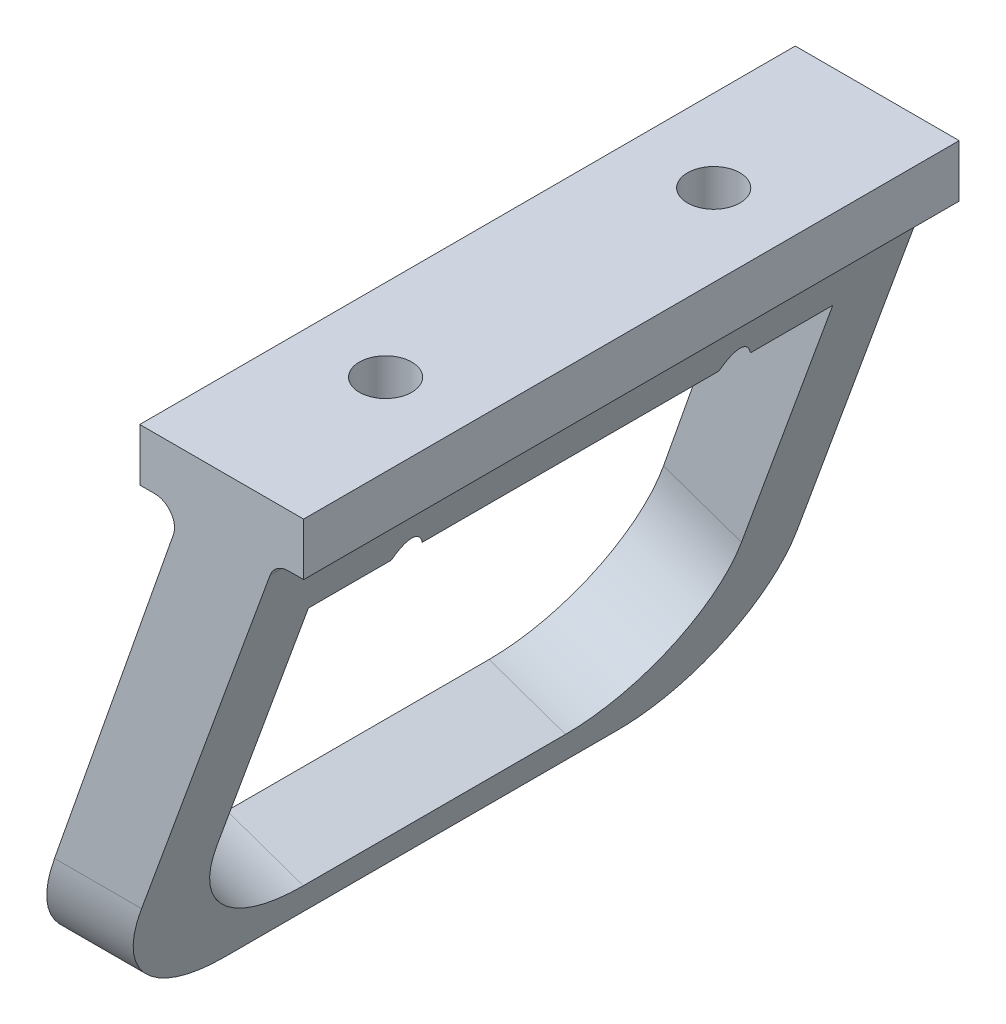
SolidWorks part; units mm, degrees
material "PETG"
ref_plane "Front Plane" through (0, 0, 0) normal (0, 0, 1) x (1, 0, 0)
ref_plane "Top Plane" through (0, 0, 0) normal (0, 1, 0) x (1, 0, 0)
ref_plane "Right Plane" through (0, 0, 0) normal (1, 0, 0) x (0, 0, -1)
sketch "Sketch1" plane through (0, 0, 0) normal (0, 0, 1) x (1, 0, 0)
  line L0 (0, 0) -> (0, 8)
  line L1 (0, 8) -> (25, 8)
  line L2 (25, 8) -> (25, 0)
  line L3 (25, 0) -> (22.7, 0)
  line L4 (19.8809, -1.9739) -> (-7, -75.8287)
  line L5 (-7, -75.8287) -> (-20, -75.8287)
  line L6 (-20, -75.8287) -> (5.1317, -3.9906)
  line L7 (2.3, 0) -> (0, 0)
  arc A2 (22.7, 0) -> (19.8809, -1.9739) centre (22.7, -3) ccw
  arc A3 (5.1317, -3.9906) -> (2.3, 0) centre (2.3, -3) ccw
  point P11 (20.5994, 0)
  point P14 (20.5994, 0)
  point P17 (6.5278, 0)
  dimension "D5" = 5.3
  dimension "D6" = 13
  dimension "D3" = 19.7
  dimension "D1" = 3
  dimension "D2" = 8
  dimension "D4" = 20
  dimension "D7" = 45
extrude "Boss-Extrude2" add sketch "Sketch1" against normal blind 100 contours L4 L5 L6 A3 L7 L0 L1 L2 L3 A2
sketch "Sketch3" plane through (5.816, -2.0347, 0) normal (-0.9439, 0.3302, 0) x (0, 0, 1)
  line L0 (-100, 7.5512) -> (0, 7.5512) construction
  line L1 (-90, -7.4488) -> (-10, -7.4488)
  line L2 (-90, -7.4488) -> (-90, -48.1794)
  line L3 (-70, -68.1794) -> (-30, -68.1794)
  line L4 (-10, -7.4488) -> (-10, -48.1794)
  line L5 (-50, 9.1944) -> (-50, -58.8347) construction
  line L6 (-100, -78.1794) -> (0, -78.1794) construction
  arc A0 (-30, -68.1794) -> (-10, -48.1794) centre (-30, -48.1794) ccw
  arc A1 (-90, -48.1794) -> (-70, -68.1794) centre (-70, -48.1794) ccw
  dimension "D6" = 20
  dimension "D1" = 15
  dimension "D2" = 80
  dimension "D3" = 50
  dimension "D4" = 40
  dimension "D5" = 10
extrude "Cut-Extrude1" cut sketch "Sketch3" against normal through all
fillet "Fillet1" radius 20 2 edges at (-13.5, -75.8287, 0) (-13.5, -75.8287, -100)
sketch "Sketch4" plane through (0, 8, 0) normal (0, 1, 0) x (1, 0, 0)
  line L0 (12.5, 142.0949) -> (12.5, -31.0559) construction
  line L1 (34.7446, 75) -> (-32.487, 75) construction
  line L2 (41.7725, 25) -> (-19.1727, 25) construction
  line L3 (0, 100) -> (0, 0) construction
  line L4 (0, 100) -> (25, 100) construction
  line L5 (25, 100) -> (25, 0) construction
  line L6 (0, 0) -> (25, 0) construction
  point P14 (12.5, 25)
  point P16 (12.5, 55.5195)
  dimension "D1" = 12.5
  dimension "D2" = 25
  dimension "D3" = 50
hole_wizard "Ø1.0mm Dowel Hole2" positions "Sketch7" profile "Sketch8" hole size "Ø1.0" standard "ISO" end condition through all
sketch "Sketch7" plane through (0, 8, 0) normal (0, 1, 0) x (1, 0, 0)
  point P0 (12.5251, 75.0333)
  point P2 (12.5, 25)
  point P5 (52.4975, 47.6674)
sketch "Sketch8" plane through (12.5251, 8, -75.0333) normal (1, 0, 0) x (0, 0, 1)
  line L0 (0, 0) -> (0, 83.8287)
  line L1 (0, 83.8287) -> (4, 83.8287)
  line L2 (4, 83.8287) -> (4, 0)
  line L5 (4, 0) -> (0, 0)
  line L11 (0, -6.35) -> (0, 107.95) construction
  dimension "Thru Hole Dia." = 8
  dimension "Thru Hole Depth" = 83.8287
